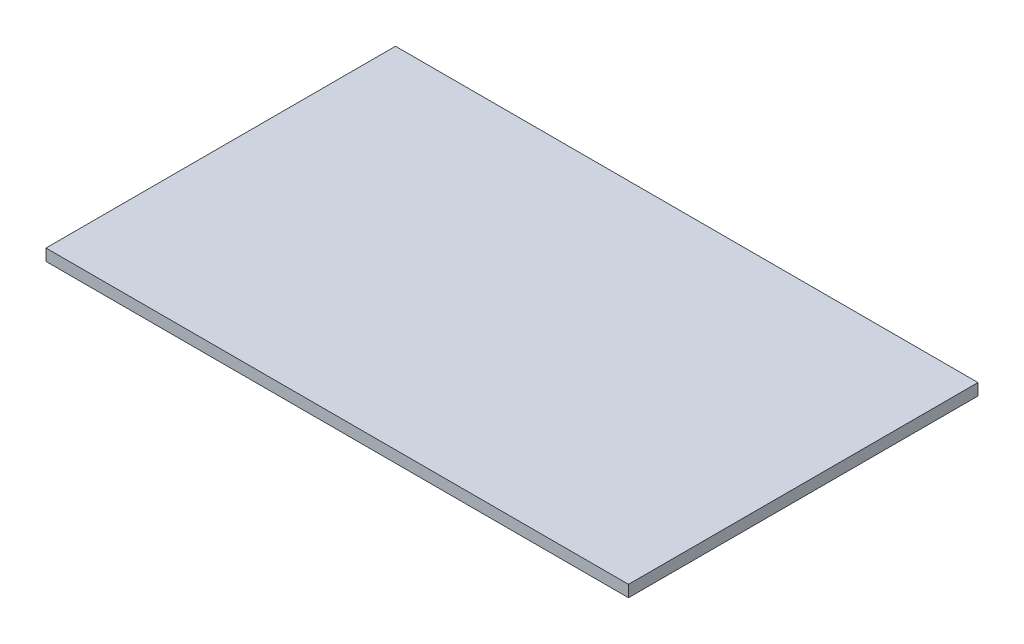
SolidWorks part; units mm, degrees
ref_plane "Front Plane" through (0, 0, 0) normal (0, 0, 1) x (1, 0, 0)
ref_plane "Top Plane" through (0, 0, 0) normal (0, 1, 0) x (1, 0, 0)
ref_plane "Right Plane" through (0, 0, 0) normal (1, 0, 0) x (0, 0, -1)
sketch "Sketch1" plane through (0, 0, 0) normal (0, 1, 0) x (1, 0, 0)
  line L1 (-250, -150) -> (250, -150)
  line L2 (-250, -150) -> (-250, 150)
  line L3 (-250, 150) -> (250, 150)
  line L4 (250, -150) -> (250, 150)
  line L5 (-250, -150) -> (250, 150) construction
  line L6 (-250, 150) -> (250, -150) construction
  point P0 (0, 0)
  dimension "D1" = 300
  dimension "D2" = 500
extrude "Boss-Extrude1" add sketch "Sketch1" along normal blind 10
